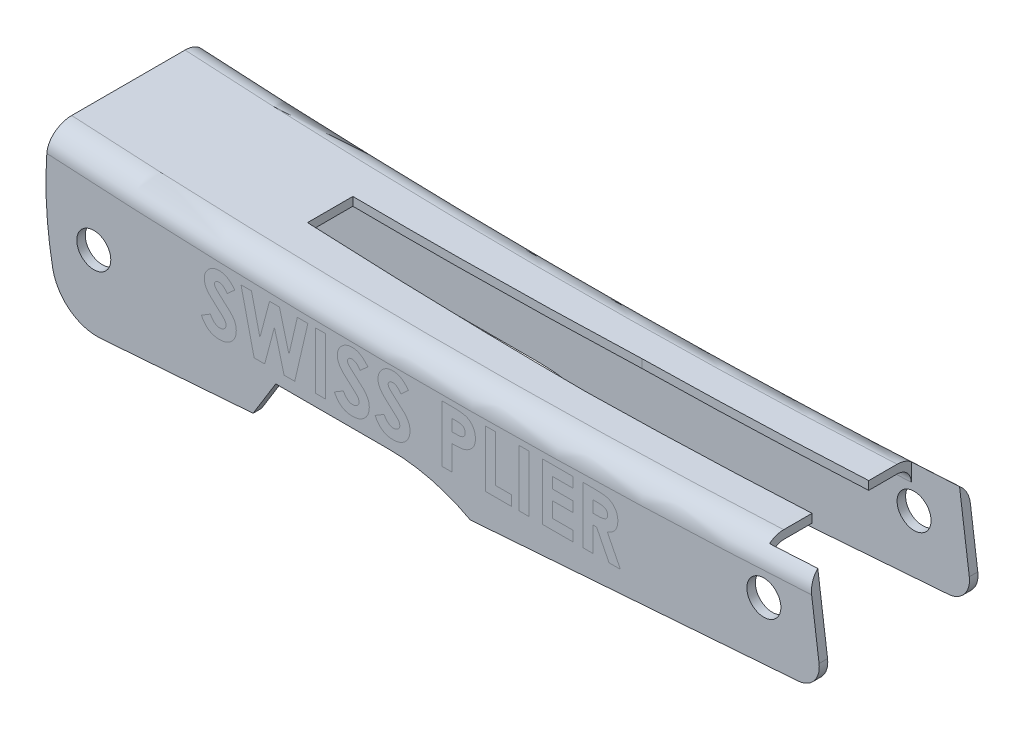
SolidWorks part; units mm, degrees
ref_plane "Front Plane" through (0, 0, 0) normal (0, 0, 1) x (1, 0, 0)
ref_plane "Top Plane" through (0, 0, 0) normal (0, 1, 0) x (1, 0, 0)
ref_plane "Right Plane" through (0, 0, 0) normal (1, 0, 0) x (0, 0, -1)
sketch "Sketch3" plane through (0, 0, 0) normal (0, 0, 1) x (1, 0, 0)
  line L0 (0, 0) -> (67, 0)
  line L1 (67, 0) -> (68.2, -9)
  line L2 (68.2, -9) -> (1.2, -14)
  line L3 (1.2, -14) -> (0, 0)
  arc A0 (67, 0) -> (0, 0) centre (33.5, 560.625) cw
  arc A1 (1.2, -14) -> (0, 0) centre (33.0128, -4.2218) cw
  point P7 (33.5, -1)
  point P8 (-0.1473, -7.0641)
  dimension "D1" = 67
  dimension "D2" = 9
  dimension "D3" = 1.2
  dimension "D4" = 1.2
  dimension "D5" = 14
  dimension "D6" = 1
  dimension "D7" = 0.75
extrude "Boss-Extrude1" add sketch "Sketch3" along normal mid plane 14 contours L1 A0 L3 L2 | A1 L3
fillet "Fillet1" radius 2 3 edges at (68.2, -9, 0) (33.5, -1, -7) (33.5, -1, 7)
fillet "Fillet2" radius 4 1 edges at (1.2, -14, 0)
shell "Shell1" thickness 0.75
sketch "Sketch4" plane through (0, 0, 7) normal (0, 0, 1) x (1, 0, 0)
  circle A0 centre (3.95, -7.3) radius 1.5
  circle A1 centre (63.05, -4.3) radius 1.5
  dimension "D1" = 3
  dimension "D2" = 3.95
  dimension "D3" = 7.3
  dimension "D4" = 3.95
  dimension "D5" = 4.3
extrude "Cut-Extrude1" cut sketch "Sketch4" against normal through all
sketch "Sketch5" plane through (0, 0, 0) normal (0, 1, 0) x (1, 0, 0)
  line L0 (0, 0) -> (71.1269, 0) construction
  line L1 (17.8, -2) -> (17.8, 2)
  line L2 (17.8, 2) -> (42.8, 2.5)
  line L3 (42.8, 2.5) -> (62.8, 2.5)
  line L4 (62.8, 2.5) -> (62.8, 6.25)
  line L5 (62.8, 6.25) -> (67.8, 6.25)
  line L7 (67.8, 6.25) -> (67.8, -6.25)
  line L9 (67, -5) -> (67, 5) construction
  line L10 (67.265, 6.25) -> (67.9199, 6.25) construction
  line L11 (62.8, -6.25) -> (67.8, -6.25)
  line L12 (62.8, -2.5) -> (62.8, -6.25)
  line L13 (42.8, -2.5) -> (62.8, -2.5)
  line L14 (17.8, -2) -> (42.8, -2.5)
  point P14 (0, 0)
  point P15 (0, 0)
  point P16 (0, 0)
  point P18 (67.8, 0)
  point P22 (17.8, 0)
  dimension "D1" = 5
  dimension "D2" = 0.8
  dimension "D3" = 3.75
  dimension "D4" = 25
  dimension "D5" = 2
  dimension "D6" = 50
extrude "Cut-Extrude2" cut sketch "Sketch5" against normal blind 14
sketch "Sketch6" plane through (0, 0, 7) normal (0, 0, 1) x (1, 0, 0)
  line L0 (18, -12.7463) -> (20, -9.5)
  line L1 (66.0862, -9.1577) -> (4.5574, -13.7494) construction
  line L2 (20, -9.5) -> (30, -9.5)
  line L3 (37.1556, -11.3167) -> (18, -12.7463)
  line L4 (0, 0) -> (67, 0) construction
  arc A0 (30, -9.5) -> (37.1556, -11.3167) centre (30, -24.5) cw
  dimension "D5" = 15
  dimension "D1" = 18
  dimension "D2" = 9.5
  dimension "D3" = 20
  dimension "D4" = 30
extrude "Cut-Extrude3" cut sketch "Sketch6" against normal through all
sketch "Sketch7" plane through (0, 0, 7) normal (0, 0, 1) x (1, 0, 0)
  line L0 (12.1298, -9.0256) -> (52.1136, -8.4664) construction
  text T0 "SWISS PLIER" font "Century Gothic" height 5
split line "Split Line1"
